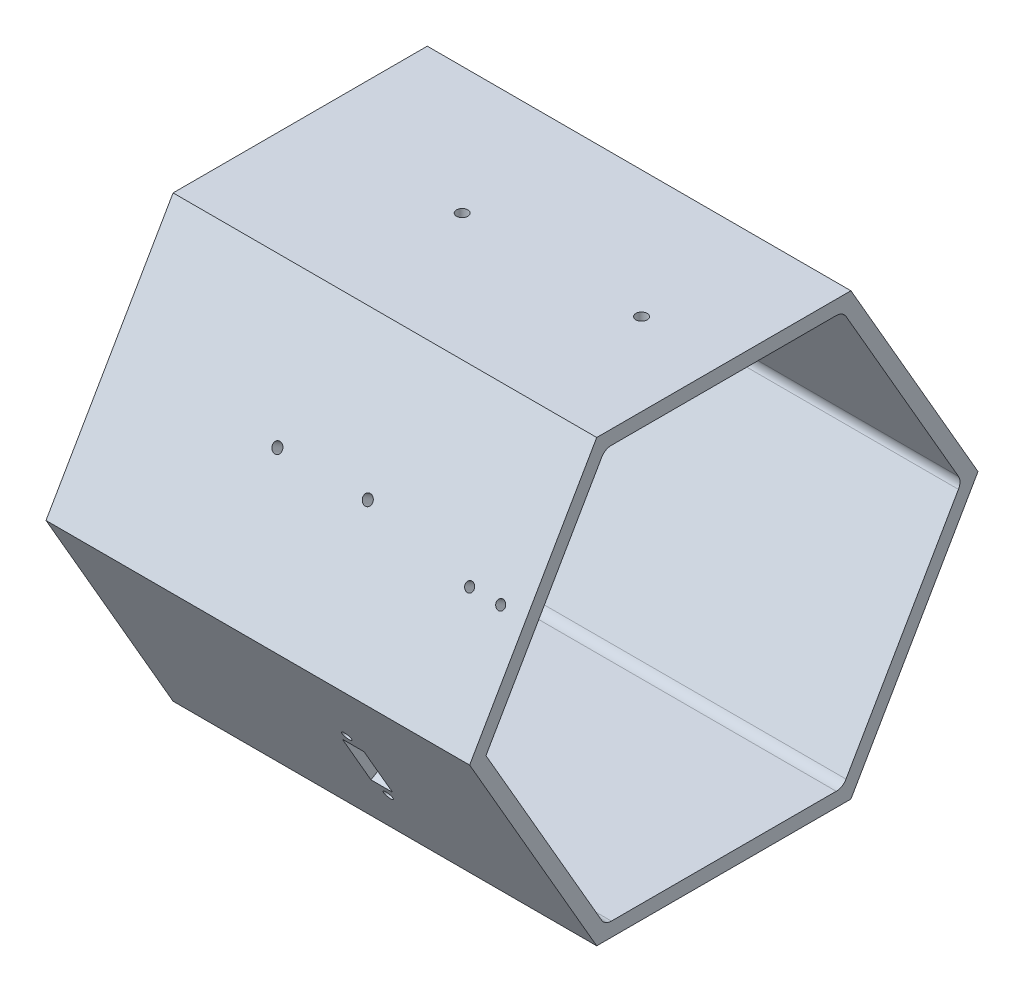
SolidWorks part; units mm, degrees
other "Markup1"
sketch "Sketch8"
ref_plane "Front Plane" through (0, 0, 0) normal (0, 0, 1) x (1, 0, 0)
ref_plane "Top Plane" through (0, 0, 0) normal (0, 1, 0) x (1, 0, 0)
ref_plane "Right Plane" through (0, 0, 0) normal (1, 0, 0) x (0, 0, -1)
sketch "Sketch1" plane through (0, 0, 0) normal (1, 0, 0) x (0, 0, -1)
  line L1 (90, 0) -> (45, 77.9423)
  line L2 (45, 77.9423) -> (-45, 77.9423)
  line L3 (-45, 77.9423) -> (-90, 0)
  line L4 (-90, 0) -> (-45, -77.9423)
  line L5 (-45, -77.9423) -> (45, -77.9423)
  line L6 (45, -77.9423) -> (90, 0)
  circle A0 centre (0, 0) radius 77.9423 construction
  dimension "D1" = 180
extrude "Boss-Extrude1" add sketch "Sketch1" along normal blind 200
sketch "Sketch2" plane through (200, 0, 0) normal (1, 0, 0) x (0, 0, -1)
  line L0 (-45, 77.9423) -> (-90, 0) construction
  line L1 (84.2265, 0) -> (42.1132, 72.9423)
  line L2 (42.1132, 72.9423) -> (-42.1132, 72.9423)
  line L3 (-42.1132, 72.9423) -> (-84.2265, 0)
  line L4 (-84.2265, 0) -> (-42.1132, -72.9423)
  line L5 (-42.1132, -72.9423) -> (42.1132, -72.9423)
  line L6 (42.1132, -72.9423) -> (84.2265, 0)
  circle A0 centre (0, 0) radius 72.9423 construction
  dimension "D1" = 5
extrude "Cut-Extrude1" cut sketch "Sketch2" against normal blind 195
sketch "Sketch5" plane through (0, -38.9711, 67.5) normal (0, -0.5, 0.866) x (1, 0, 0)
  line L0 (20, 45) -> (20, -45) construction
  line L1 (200, 45) -> (0, 45) construction
  line L2 (200, -45) -> (0, -45) construction
  line L3 (65, 45) -> (65, -45) construction
  line L4 (0, 45) -> (0, -45) construction
  line L5 (73.65, -5) -> (64, -5) construction
  line L6 (65, 5.1) -> (72.65, 5.1)
  line L7 (65, 5.1) -> (65, -15.1)
  line L8 (65, -15.1) -> (72.65, -15.1)
  line L9 (72.65, 5.1) -> (72.65, -15.1)
  line L10 (65, 5.1) -> (72.65, -15.1) construction
  line L11 (65, -15.1) -> (72.65, 5.1) construction
  line L12 (64, -15.5) -> (73.65, -15.5) construction
  line L13 (64, -15.5) -> (64, 5.5) construction
  line L14 (64, 5.5) -> (73.65, 5.5) construction
  line L15 (73.65, -15.5) -> (73.65, 5.5) construction
  line L16 (68.825, 14) -> (68.825, 5.5) construction
  line L17 (72.575, 9.75) -> (65.075, 9.75) construction
  line L18 (66.95, 6.5024) -> (70.7, 6.5024) construction
  line L19 (70.7, 6.5024) -> (72.575, 9.75) construction
  line L20 (72.575, 9.75) -> (70.7, 12.9976) construction
  line L21 (70.7, 12.9976) -> (66.95, 12.9976) construction
  line L22 (66.95, 12.9976) -> (65.075, 9.75) construction
  line L23 (65.075, 9.75) -> (66.95, 6.5024) construction
  arc A2 (73.65, 5.5) -> (64, 5.5) centre (68.825, 8.3806) ccw construction
  circle A3 centre (68.825, 9.75) radius 3.2476 construction
  circle A4 centre (68.825, 9.75) radius 1.65
  circle A6 centre (68.825, -19.75) radius 1.65
  point P14 (68.825, -5)
  point P15 (68.825, -5)
  dimension "D11" = 8.5
  dimension "D12" = 3.3
  dimension "D1" = 20
  dimension "D2" = 65
  dimension "D3" = 39.9
  dimension "D4" = 20.2
  dimension "D5" = 7.65
  dimension "D6" = 29.9
  dimension "D7" = 9.65
  dimension "D8" = 21
  dimension "D9" = 1
  dimension "D10" = 0.4
extrude "Cut-Extrude4" cut sketch "Sketch5" against normal blind 70
sketch "Sketch7" plane through (5, 0, 0) normal (1, 0, 0) x (0, 0, -1)
  line L0 (42.1132, 72.9423) -> (-42.1132, -72.9423) construction
  line L1 (-42.1132, 72.9423) -> (42.1132, -72.9423) construction
  line L2 (84.2265, 0) -> (-84.2265, 0) construction
  circle A0 centre (0, 0) radius 4.5
  circle A1 centre (60, 0) radius 3
  circle A2 centre (30, 51.9615) radius 3
  circle A3 centre (-30, 51.9615) radius 3
  circle A4 centre (-60, 0) radius 3
  circle A5 centre (-30, -51.9615) radius 3
  circle A6 centre (30, -51.9615) radius 3
  dimension "D1" = 9
  dimension "D2" = 6
  dimension "D3" = 6
  dimension "D4" = 6
  dimension "D5" = 6
  dimension "D6" = 6
  dimension "D7" = 6
  dimension "D8" = 60
  dimension "D9" = 60
  dimension "D10" = 60
  dimension "D11" = 60
  dimension "D12" = 60
  dimension "D13" = 60
extrude "Cut-Extrude6" cut sketch "Sketch7" against normal blind 70
fillet "Fillet1" radius 4 11 edges at (102.5, 0, -84.2265) (5, -72.9423, 0) (5, -36.4711, -63.1699) (102.5, -72.9423, -42.1132) (102.5, -72.9423, 42.1132) (5, -36.4711, 63.1699) (5, 36.4711, 63.1699) (102.5, 72.9423, 42.1132) (5, 72.9423, 0) (102.5, 72.9423, -42.1132) (5, 36.4711, -63.1699)
sketch "Sketch9" plane through (200, 0, 0) normal (1, 0, 0) x (0, 0, -1)
  line L0 (45, 77.9423) -> (90, 0)
  line L1 (90, 0) -> (45, -77.9423)
  line L2 (45, -77.9423) -> (-45, -77.9423)
  line L3 (-45, -77.9423) -> (-90, 0)
  line L4 (-90, 0) -> (-45, 77.9423)
  line L5 (-45, 77.9423) -> (45, 77.9423)
extrude "Cut-Extrude7" cut sketch "Sketch9" against normal blind 70
sketch "Sketch10" plane through (0, 38.9711, 67.5) normal (0, 0.5, 0.866) x (1, 0, 0)
  line L0 (130, 45) -> (130, -45) construction
  line L4 (130, 45) -> (0, 45) construction
  line L5 (150.288, -5) -> (110, -5) construction
  line L6 (130, -45) -> (0, -45) construction
  circle A0 centre (110, -5) radius 1.6
  circle A1 centre (121, -5) radius 1.6
  dimension "D1" = 3.2
  dimension "D4" = 3.2
  dimension "D2" = 20
  dimension "D3" = 50
  dimension "D5" = 11
extrude "Cut-Extrude8" cut sketch "Sketch10" against normal blind 6
sketch "Sketch11" plane through (0, 0, 0) normal (-1, 0, 0) x (0, 0, 1)
  line L0 (90, 0) -> (45, 77.9423)
  line L1 (45, 77.9423) -> (-45, 77.9423)
  line L2 (-45, 77.9423) -> (-90, 0)
  line L3 (-90, 0) -> (-45, -77.9423)
  line L4 (-45, -77.9423) -> (45, -77.9423)
  line L5 (45, -77.9423) -> (90, 0)
  line L7 (84.2265, 0) -> (42.1132, 72.9423)
  line L8 (42.1132, 72.9423) -> (-42.1132, 72.9423)
  line L9 (-42.1132, 72.9423) -> (-84.2265, 0)
  line L10 (-84.2265, 0) -> (-42.1132, -72.9423)
  line L11 (-42.1132, -72.9423) -> (42.1132, -72.9423)
  line L12 (42.1132, -72.9423) -> (84.2265, 0)
  circle A0 centre (0, 0) radius 72.9423 construction
  dimension "D1" = 5
extrude "Boss-Extrude2" add sketch "Sketch11" along normal blind 20
sketch "Sketch12" plane through (0, 77.9423, 0) normal (0, 1, 0) x (1, 0, 0)
  line L0 (-20, 0) -> (130, 0) construction
  line L3 (130, 47.5) -> (-2, 47.5) construction
  line L8 (130, 47.5) -> (130, -47.5) construction
  line L9 (130, -47.5) -> (-2, -47.5) construction
  line L10 (-2, 47.5) -> (-2, -47.5) construction
  line L11 (64, -47.5) -> (64, 47.5) construction
  line L12 (130, 0) -> (-2, 0) construction
  line L13 (-20, -45) -> (-20, 45) construction
  line L14 (130, 45) -> (130, -45) construction
  circle A2 centre (100.87, 0) radius 2
  circle A3 centre (37.37, 0) radius 2
  point P92 (64, 0)
  dimension "D1" = 132
  dimension "D2" = 95
  dimension "D4" = 63.5
  dimension "D3" = 29.13
  dimension "D5" = 4
  dimension "D6" = 4
extrude "Cut-Extrude9" cut sketch "Sketch12" against normal blind 10
sketch "Sketch13" plane through (0, 38.9711, 67.5) normal (0, 0.5, 0.866) x (1, 0, 0)
  circle A0 centre (70.7668, 1.3415) radius 1.75
  circle A1 centre (38.7668, 1.3415) radius 1.75
  dimension "D1" = 3.5
  dimension "D2" = 32
  dimension "D3" = 3.5
extrude "Cut-Extrude10" cut sketch "Sketch13" against normal blind 10
